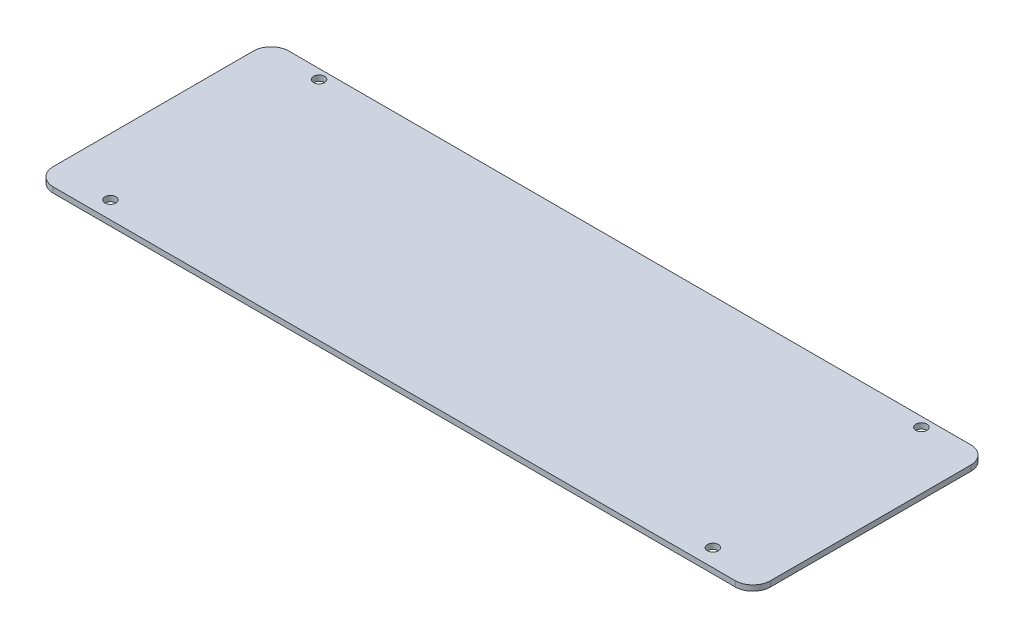
SolidWorks part; units mm, degrees
material "Custom Plastic"
ref_plane "X-Y Datum" through (0, 0, 0) normal (0, 0, 1) x (1, 0, 0)
ref_plane "X-Z Datum" through (0, 0, 0) normal (0, 1, 0) x (1, 0, 0)
ref_plane "Y-Z Datum" through (0, 0, 0) normal (1, 0, 0) x (0, 0, -1)
sketch "Sketch1" plane through (0, 0, 0) normal (0, 1, 0) x (1, 0, 0)
  line L0 (-191.0411, 2.1285) -> (-171.9911, 2.1285) construction
  line L5 (-191.0411, -118.4497) -> (-171.9911, -118.4497) construction
  line L6 (2.1259, 61.7475) -> (2.1259, -141.149) construction
  line L11 (-205.1961, -128.5025) -> (209.4479, -128.5025)
  line L12 (-205.1961, -128.5025) -> (-205.1961, 7.6044)
  line L13 (-205.1961, 7.6044) -> (209.4479, 7.6044)
  line L14 (209.4479, -128.5025) -> (209.4479, 7.6044)
  line L15 (-171.9911, 7.6044) -> (-171.9911, 2.1285) construction
  circle A4 centre (-171.9911, 2.1285) radius 3.175
  circle A5 centre (-171.9911, -118.4497) radius 3.175
  circle A6 centre (176.2429, 2.1285) radius 3.175
  circle A7 centre (176.2429, -118.4497) radius 3.175
extrude "Boss-Extrude1" add sketch "Sketch1" along normal blind 3.175
fillet "Fillet1" radius 10.16 4 edges at (209.4479, 1.5875, 128.5025) (209.4479, 1.5875, -7.6044) (-205.1961, 1.5875, 128.5025) (-205.1961, 1.5875, -7.6044)
